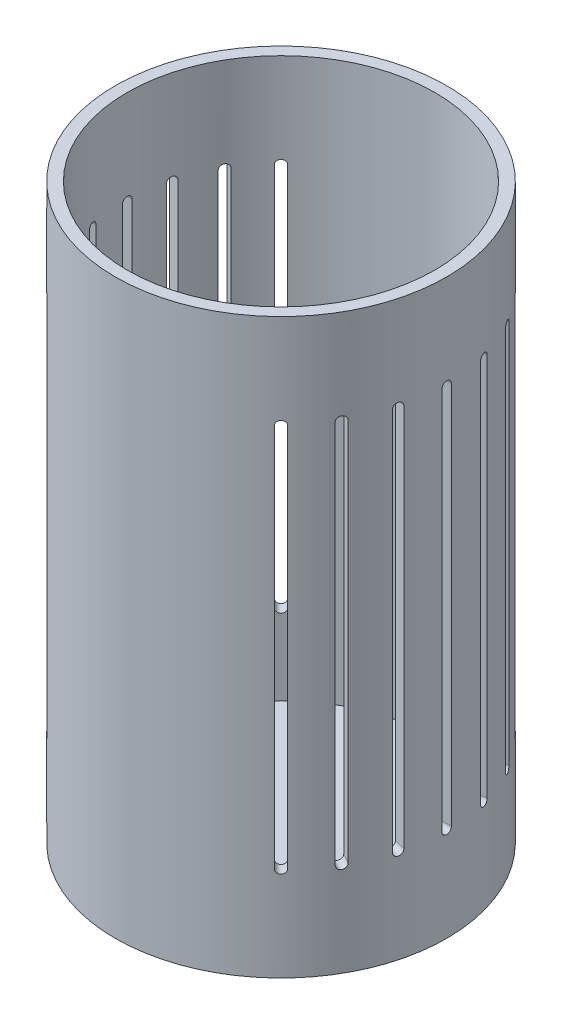
SolidWorks part; units mm, degrees
material "Rubber"
ref_plane "Front Plane" through (0, 0, 0) normal (0, 0, 1) x (1, 0, 0)
ref_plane "Top Plane" through (0, 0, 0) normal (0, 1, 0) x (1, 0, 0)
ref_plane "Right Plane" through (0, 0, 0) normal (1, 0, 0) x (0, 0, -1)
sketch "Sketch1" plane through (0, 0, 0) normal (0, 1, 0) x (1, 0, 0)
  circle A0 centre (0, 0) radius 32.5
  circle A1 centre (0, 0) radius 35
  dimension "D1" = 65
  dimension "D2" = 70
extrude "Boss-Extrude1" add sketch "Sketch1" along normal blind 121
sketch "Sketch4" plane through (0, 0, 0) normal (0, -1, 0) x (1, 0, 0)
  circle A0 centre (0, 0) radius 32.5
extrude "Boss-Extrude2" add sketch "Sketch4" against normal blind 3 separate body
sketch "Sketch5" plane through (0, 0, 0) normal (1, 0, 0) x (0, 0, -1)
  line L0 (0, 101) -> (0, 20) construction
  line L1 (1, 101) -> (1, 20)
  line L2 (-1, 101) -> (-1, 20)
  line L3 (35, 121) -> (-35, 121) construction
  line L4 (-35, 0) -> (35, 0) construction
  arc A0 (1, 101) -> (-1, 101) centre (0, 101) ccw
  arc A1 (-1, 20) -> (1, 20) centre (0, 20) ccw
  point P3 (0, 60.5)
  point P10 (0, 0)
  dimension "D3" = 1
  dimension "D1" = 20
  dimension "D2" = 20
extrude "Cut-Extrude1" cut sketch "Sketch5" against normal through all both and the other way through all
sketch "Sketch6" plane through (0, 0, 0) normal (1, 0, 0) x (0, 0, -1)
  line L0 (0, 0) -> (0, 121) construction
  line L1 (35, 121) -> (-35, 121) construction
pattern_circular "CirPattern1" count 4 every 15 about axis through (0, 0, 0) along (0, 1, 0) of "Cut-Extrude1"
